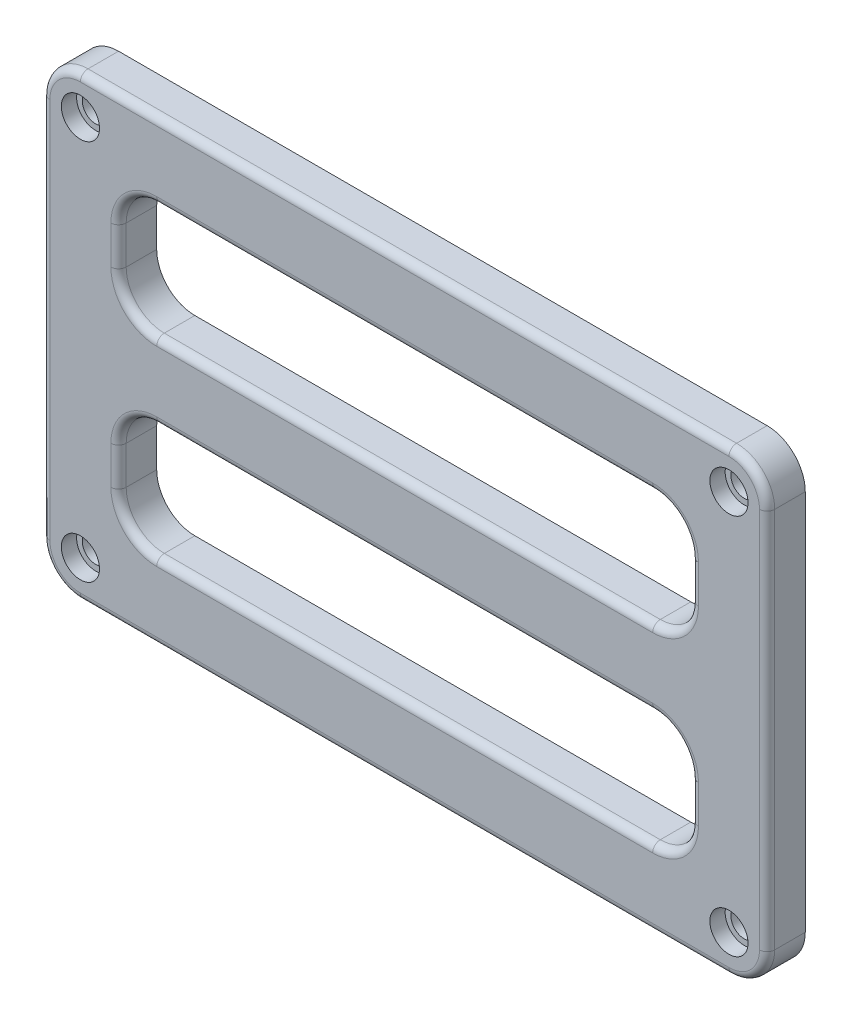
SolidWorks part; units mm, degrees
ref_plane "Front Plane" through (0, 0, 0) normal (0, 0, 1) x (1, 0, 0)
ref_plane "Top Plane" through (0, 0, 0) normal (0, 1, 0) x (1, 0, 0)
ref_plane "Right Plane" through (0, 0, 0) normal (1, 0, 0) x (0, 0, -1)
sketch "Sketch1" plane through (0, 0, 0) normal (0, 0, 1) x (1, 0, 0)
  line L0 (0, 0) -> (75, 0)
  line L1 (75, 0) -> (75, 40)
  line L2 (75, 40) -> (0, 40)
  line L3 (0, 40) -> (0, 0)
  line L4 (-10, -10) -> (85, -10)
  line L5 (85, -10) -> (85, 50)
  line L6 (85, 50) -> (-10, 50)
  line L7 (-10, 50) -> (-10, -10)
  dimension "D1" = 75
  dimension "D2" = 40
  dimension "D3" = 10
  dimension "D4" = 10
  dimension "D5" = 10
  dimension "D6" = 10
extrude "Boss-Extrude1" add sketch "Sketch1" along normal blind 5
sketch "Sketch2" plane through (0, 0, 5) normal (0, 0, 1) x (1, 0, 0)
  line L1 (0, 25) -> (75, 25)
  line L4 (0, 20) -> (0, 25)
  line L5 (0, 40) -> (0, 0) construction
  line L6 (0, 20) -> (0, 15)
  line L10 (75, 20) -> (75, 25)
  line L11 (75, 0) -> (75, 40) construction
  line L12 (75, 20) -> (75, 15)
  line L21 (0, 15) -> (75, 15)
  dimension "D3" = 5
  dimension "D4" = 5
  dimension "D5" = 5
  dimension "D6" = 5
extrude "Boss-Extrude2" add sketch "Sketch2" against normal blind 5
sketch "Sketch5" plane through (0, 0, 5) normal (0, 0, 1) x (1, 0, 0)
  line L4 (-10, 50) -> (-10, -10) construction
  line L5 (85, -10) -> (85, 50) construction
  line L6 (-10, -10) -> (85, -10) construction
  line L7 (85, 50) -> (-10, 50) construction
  line L8 (85, 50) -> (-10, 50) construction
  line L9 (85, -10) -> (85, 50) construction
  line L10 (-10, -10) -> (85, -10) construction
  line L11 (-10, 50) -> (-10, -10) construction
  circle A0 centre (-5, 45) radius 1.75
  circle A1 centre (80, 45) radius 1.75
  circle A2 centre (80, -5) radius 1.75
  circle A3 centre (-5, -5) radius 1.75
  dimension "D1" = 3.5
  dimension "D2" = 3.5
  dimension "D3" = 3.5
  dimension "D4" = 3.5
  dimension "D5" = 5
  dimension "D6" = 5
  dimension "D7" = 5
  dimension "D8" = 5
  dimension "D9" = 5
  dimension "D10" = 5
  dimension "D11" = 5
  dimension "D12" = 5
extrude "Cut-Extrude2" cut sketch "Sketch5" against normal through all
sketch "Sketch6" plane through (0, 0, 5) normal (0, 0, 1) x (1, 0, 0)
  circle A0 centre (-5, 45) radius 2.5
  circle A1 centre (80, 45) radius 2.5
  circle A2 centre (80, -5) radius 2.5
  circle A3 centre (-5, -5) radius 2.5
  dimension "D1" = 5
  dimension "D2" = 5
  dimension "D3" = 5
  dimension "D4" = 5
extrude "Cut-Extrude3" cut sketch "Sketch6" against normal blind 2
fillet "Fillet1" radius 5 12 edges at (0, 15, 2.5) (75, 0, 2.5) (75, 15, 2.5) (0, 0, 2.5) (0, 25, 2.5) (75, 25, 2.5) (75, 40, 2.5) (0, 40, 2.5) (-10, 50, 2.5) (85, 50, 2.5) (85, -10, 2.5) (-10, -10, 2.5)
fillet "Fillet2" radius 1 24 edges at (1.4645, 13.5355, 5) (0, 7.5, 5) (1.4645, 1.4645, 5) (37.5, 0, 5) (73.5355, 1.4645, 5) (75, 7.5, 5) (73.5355, 13.5355, 5) (73.5355, 38.5355, 5) (75, 32.5, 5) (73.5355, 26.4645, 5) (37.5, 25, 5) (1.4645, 26.4645, 5) (0, 32.5, 5) (1.4645, 38.5355, 5) (-8.5355, -8.5355, 5) (-10, 20, 5) (-8.5355, 48.5355, 5) (37.5, 50, 5) (83.5355, 48.5355, 5) (85, 20, 5) (83.5355, -8.5355, 5) (37.5, 15, 5) (37.5, 40, 5) (37.5, -10, 5)
